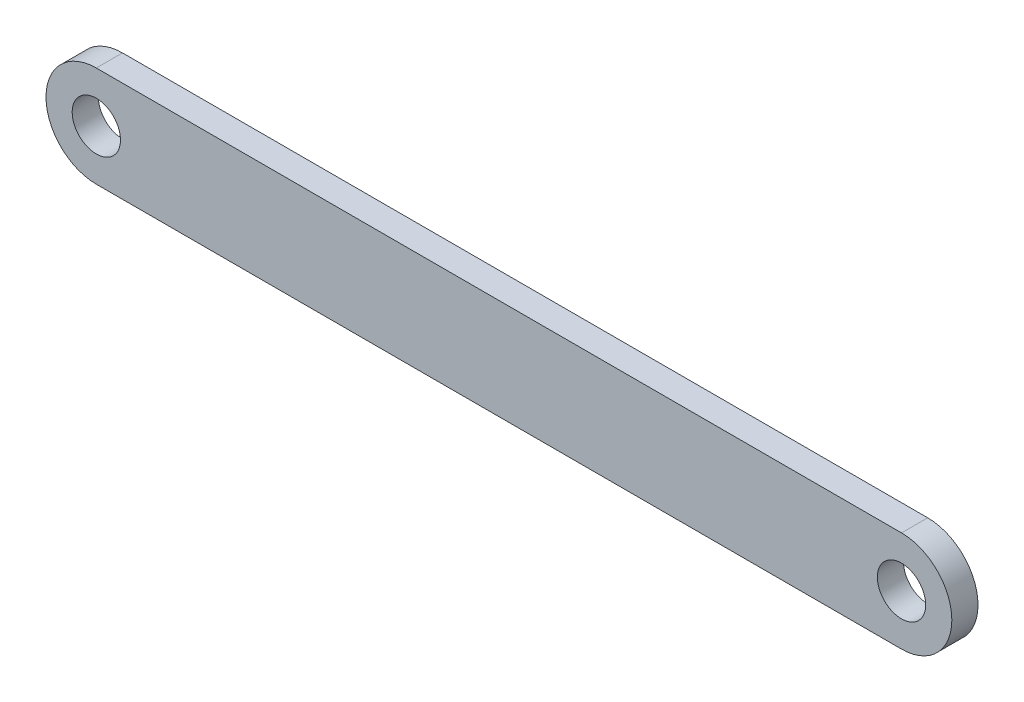
SolidWorks part; units mm, degrees
ref_plane "Front Plane" through (0, 0, 0) normal (0, 0, 1) x (1, 0, 0)
ref_plane "Top Plane" through (0, 0, 0) normal (0, 1, 0) x (1, 0, 0)
ref_plane "Right Plane" through (0, 0, 0) normal (1, 0, 0) x (0, 0, -1)
sketch "Sketch1" plane through (0, 0, 0) normal (0, 0, 1) x (1, 0, 0)
  line L0 (0, 0) -> (200, 0) construction
  line L1 (0, 12.5) -> (200, 12.5)
  line L2 (0, -12.5) -> (200, -12.5)
  arc A0 (0, 12.5) -> (0, -12.5) centre (0, 0) ccw
  arc A1 (200, -12.5) -> (200, 12.5) centre (200, 0) ccw
  circle A2 centre (0, 0) radius 6
  circle A3 centre (200, 0) radius 6
  point P3 (100, 0)
  dimension "D2" = 12.5
  dimension "D3" = 12
  dimension "D4" = 12
  dimension "D1" = 200
extrude "Boss-Extrude1" add sketch "Sketch1" along normal mid plane 6.5
